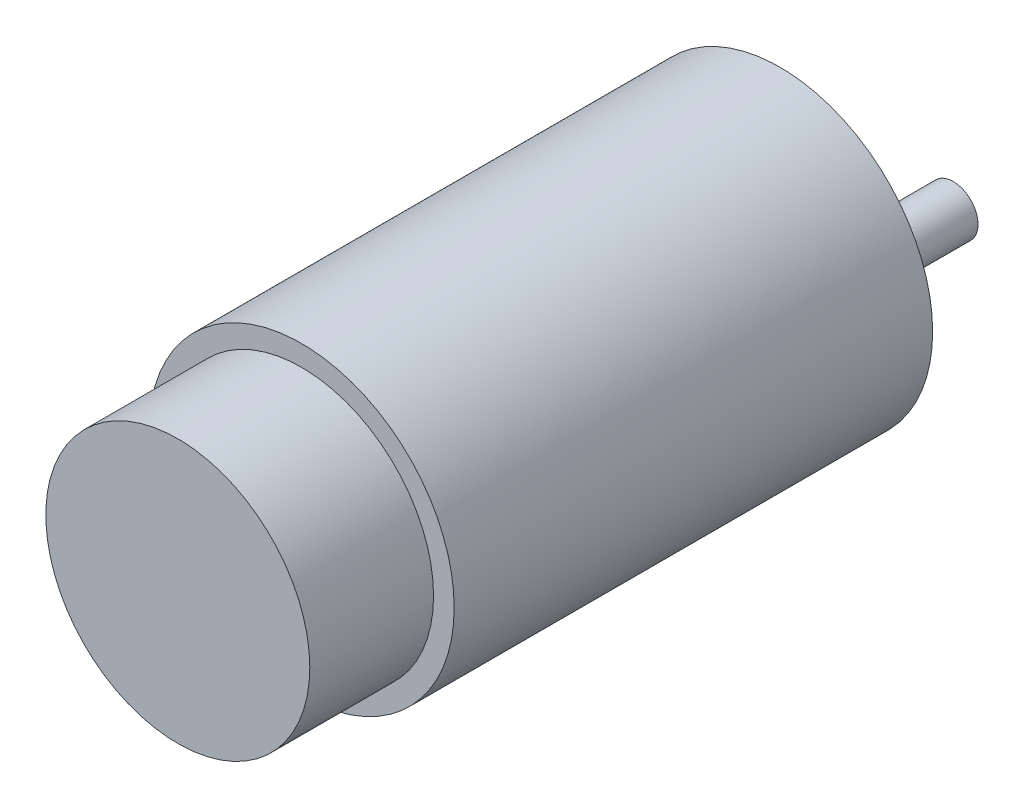
SolidWorks part; units mm, degrees
ref_plane "前视基准面" through (0, 0, 0) normal (0, 0, 1) x (1, 0, 0)
ref_plane "上视基准面" through (0, 0, 0) normal (0, 1, 0) x (1, 0, 0)
ref_plane "右视基准面" through (0, 0, 0) normal (1, 0, 0) x (0, 0, -1)
sketch "草图1" plane through (0, 0, 0) normal (0, 0, 1) x (1, 0, 0)
  circle A0 centre (0, 0) radius 18.5
  dimension "D1" = 37
extrude "凸台-拉伸1" add sketch "草图1" along normal blind 58
sketch "草图2" plane through (0, 0, 0) normal (0, 0, -1) x (-1, 0, 0)
  circle A1 centre (0, -7) radius 6
  dimension "D1" = 12
  dimension "D2" = 7
extrude "凸台-拉伸2" add sketch "草图2" along normal blind 6
sketch "草图3" plane through (0, 0, -6) normal (0, 0, -1) x (-1, 0, 0)
  line L0 (1.8, -9.4) -> (-1.8, -9.4)
  circle A0 centre (0, -7) radius 3
  circle A1 centre (0, -7) radius 6 construction
  dimension "D1" = 6
  dimension "D2" = 2.4
extrude "凸台-拉伸3" add sketch "草图3" along normal offset from surface (15 mm away) 21
sketch "草图4" plane through (0, 0, 58) normal (0, 0, 1) x (1, 0, 0)
  circle A0 centre (0, 0) radius 16
  dimension "D1" = 32
extrude "凸台-拉伸4" add sketch "草图4" along normal blind 15 separate body
sketch "草图5" plane through (0, 0, -6) normal (0, 0, -1) x (-1, 0, 0)
  circle A0 centre (0, -7) radius 3
  circle A1 centre (0, -7) radius 6 construction
extrude "凸台-拉伸5" add sketch "草图5" along normal offset from surface (3 mm away) 12 up to face at (0, -6.7, -21)
sketch "草图6" plane through (0, 0, 0) normal (0, 0, -1) x (-1, 0, 0)
  line L0 (0, 0) -> (-7.75, -13.4234) construction
  line L1 (0, -1000) -> (0, 49000) construction
  line L2 (0, 0) -> (20.3765, 0) construction
  circle A0 centre (0, 0) radius 15.5 construction
  circle A4 centre (-7.75, -13.4234) radius 1.6
  circle A5 centre (-15.5, 0) radius 1.6
  circle A6 centre (-7.75, 13.4234) radius 1.6
  circle A7 centre (7.75, 13.4234) radius 1.6
  circle A8 centre (15.5, 0) radius 1.6
  circle A9 centre (7.75, -13.4234) radius 1.6
  point P11 (0, 0)
  point P26 (0, 0)
  dimension "D1" = 31
  dimension "D2" = 120
  dimension "D5" = 3.2
  dimension "D6" = 6
extrude "切除-拉伸1" cut sketch "草图6" against normal blind 5
